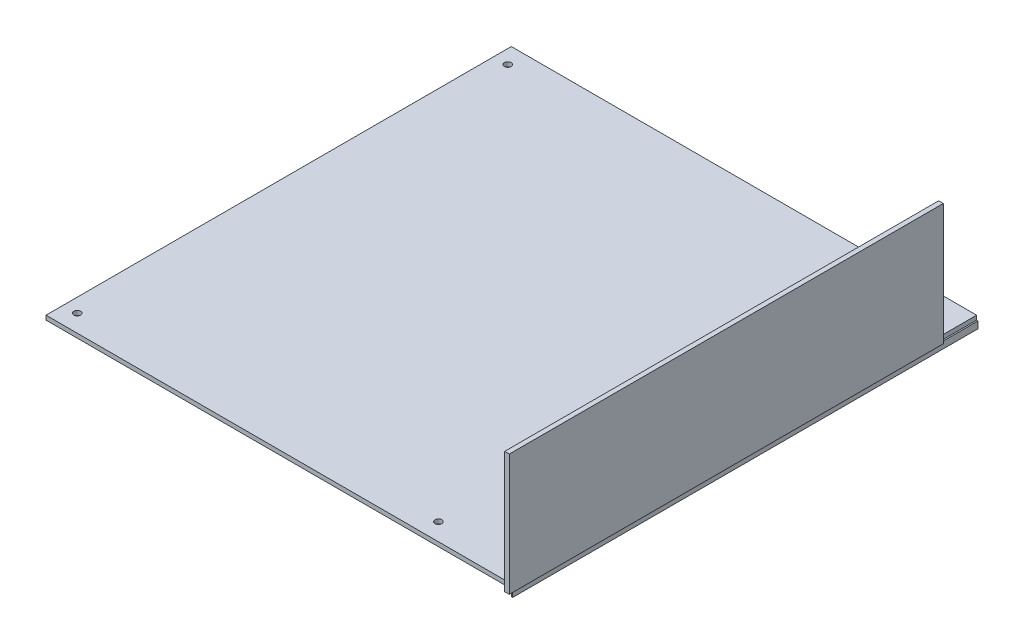
SolidWorks part; units mm, degrees
ref_plane "Front Plane" through (0, 0, 0) normal (0, 0, 1) x (1, 0, 0)
ref_plane "Top Plane" through (0, 0, 0) normal (0, 1, 0) x (1, 0, 0)
ref_plane "Right Plane" through (0, 0, 0) normal (1, 0, 0) x (0, 0, -1)
sketch "Sketch1" plane through (0, 0, 0) normal (0, 1, 0) x (1, 0, 0)
  line L1 (0, 0) -> (-170.18, 0)
  line L2 (0, 0) -> (0, 170.18)
  line L3 (0, 170.18) -> (-170.18, 170.18)
  line L4 (-170.18, 0) -> (-170.18, 170.18)
  dimension "D1" = 170.18
  dimension "D2" = 170.18
extrude "pcb" add sketch "Sketch1" along normal blind 1.57
sketch "Sketch2" plane through (0, 1.57, 1.57) normal (0, 1, 0) x (1, 0, 0)
  line L0 (-10.16, 165.4) -> (-10.16, 7.92) construction
  line L1 (0, 1.57) -> (-170.18, 1.57)
  line L2 (0, 1.57) -> (0, 171.75)
  line L3 (0, 171.75) -> (-170.18, 171.75)
  line L4 (-170.18, 1.57) -> (-170.18, 171.75)
  line L5 (-10.16, 7.92) -> (-33.02, 7.92) construction
  line L6 (-33.02, 7.92) -> (-165.1, 7.92) construction
  line L7 (-165.1, 7.92) -> (-165.1, 165.4) construction
  line L8 (-165.1, 165.4) -> (-10.16, 165.4) construction
  line L9 (-10.16, 165.4) -> (0, 165.4) construction
  line L10 (-4.8301, 157.88) -> (-4.8301, -0.87) construction
  line L11 (-10.16, 165.4) -> (-10.16, 171.75) construction
  line L14 (-170.18, 171.75) -> (0, 171.75) construction
  line L15 (0, 1.57) -> (-4.8301, 1.57) construction
  line L16 (0, 1.57) -> (0, 157.88) construction
  line L17 (0, 157.88) -> (-4.8301, 157.88) construction
  dimension "D1" = 170.18
  dimension "D2" = 170.18
  dimension "D3" = 157.48
  dimension "D4" = 22.86
  dimension "D5" = 6.35
  dimension "D6" = 10.16
  dimension "D7" = 154.94
  dimension "D9" = 2.44
  dimension "D10" = 158.75
hole_wizard "M3x0.5 Tapped Hole1" positions "3DSketch1" profile "Sketch3" tap size "M3x0.5" standard "ANSI Metric" end condition up to next
sketch3d "3DSketch1"
  point P0 (-165.1, 1.57, -163.83)
  point P3 (-10.16, 1.57, -163.83)
  point P6 (-33.02, 1.57, -6.35)
  point P9 (-165.1, 1.57, -6.35)
sketch "Sketch3" plane through (-165.1, 1.57, -163.83) normal (1, 0, 0) x (0, 0, 1)
  line L0 (0, 0) -> (0, 1.57)
  line L1 (0, 1.57) -> (1.25, 1.57)
  line L2 (1.25, 1.57) -> (1.25, 0)
  line L5 (1.25, 0) -> (0, 0)
  line L11 (0, -6.35) -> (0, 107.95) construction
  dimension "Thru Tap Drill Dia." = 2.5
  dimension "Thru Tap Drill Depth" = 1.57
cosmetic thread "Hole Thread1" parameters "D2"=3
cosmetic thread "Hole Thread2" parameters "D2"=3
cosmetic thread "Hole Thread3" parameters "D2"=3
cosmetic thread "Hole Thread4" parameters "D2"=3
sketch "Sketch5" plane through (0, 0, 0) normal (1, 0, 0) x (0, 0, -1)
  line L0 (6.35, 1.57) -> (163.83, 1.57) construction
  line L1 (156.31, 44.75) -> (-2.44, 44.75)
  line L2 (156.31, 44.75) -> (156.31, 0.3)
  line L3 (156.31, 0.3) -> (-2.44, 0.3)
  line L4 (-2.44, 44.75) -> (-2.44, 0.3)
  dimension "D1" = 158.75
  dimension "D2" = 44.45
  dimension "D3" = 1.27
extrude "io-shield" add sketch "Sketch5" along normal blind 1.7
sketch "Sketch6" plane through (0, 0, 0) normal (1, 0, 0) x (0, 0, -1)
  line L1 (0, 0) -> (170.18, 0)
  line L2 (0, 0) -> (0, -2.5)
  line L3 (0, -2.5) -> (170.18, -2.5)
  line L4 (170.18, 0) -> (170.18, -2.5)
  dimension "D1" = 2.5
extrude "io-shield-flange" add sketch "Sketch6" along normal blind 0.5 separate body
